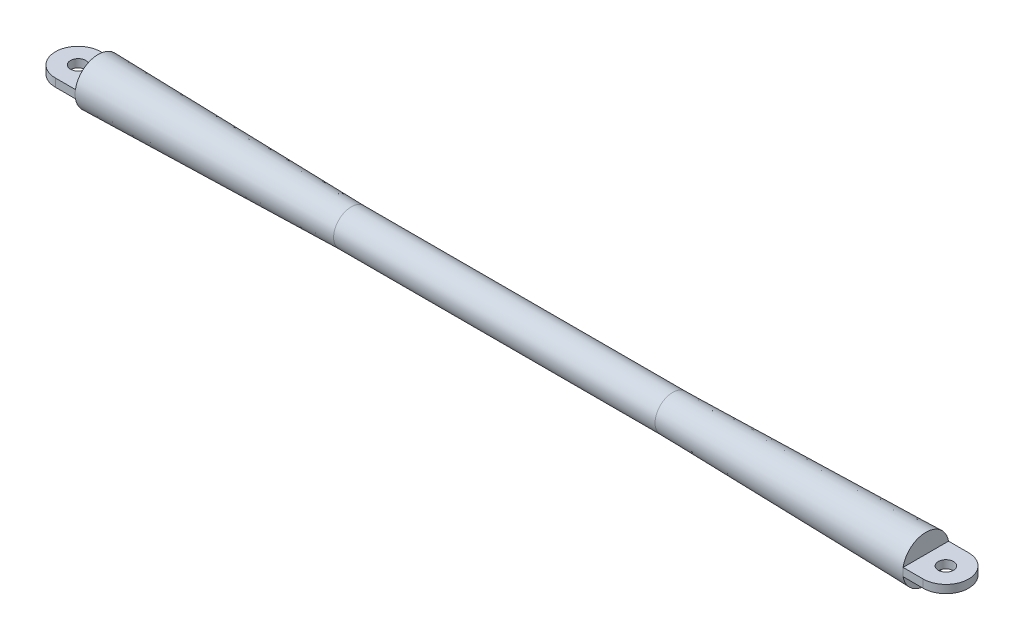
SolidWorks part; units mm, degrees
ref_plane "Front Plane" through (0, 0, 0) normal (0, 0, 1) x (1, 0, 0)
ref_plane "Top Plane" through (0, 0, 0) normal (0, 1, 0) x (1, 0, 0)
ref_plane "Right Plane" through (0, 0, 0) normal (1, 0, 0) x (0, 0, -1)
sketch "Sketch2" plane through (0, 0, 0) normal (0, 1, 0) x (1, 0, 0)
  line L0 (0, 0) -> (575, 0)
  line L1 (575, 0) -> (575, 30)
  line L2 (575, 30) -> (200, 22)
  line L3 (200, 22) -> (0, 22)
  line L4 (0, 22) -> (0, 0)
  point P3 (200.3181, 59.7349)
  dimension "D1" = 575
  dimension "D2" = 30
  dimension "D3" = 22
  dimension "D4" = 200
revolve "Revolve1" add sketch "Sketch2" angle 360 about L0
sketch "Sketch3" plane through (0, 0, 0) normal (0, 0, 1) x (1, 0, 0)
  line L0 (575, 0) -> (623.0835, 0) construction
  line L1 (515, 74.7561) -> (615.5423, 74.7561)
  line L2 (515, 74.7561) -> (515, 5)
  line L3 (515, 5) -> (615.5423, 5)
  line L4 (615.5423, 74.7561) -> (615.5423, 5)
  line L5 (575, -30) -> (575, 30) construction
  line L6 (515, -5) -> (615.5423, -5)
  line L7 (615.5423, -74.7561) -> (615.5423, -5)
  line L8 (515, -74.7561) -> (615.5423, -74.7561)
  line L9 (515, -74.7561) -> (515, -5)
  dimension "D1" = 10
  dimension "D2" = 60
extrude "Cut-Extrude1" cut sketch "Sketch3" against normal mid plane 100
sketch "Sketch4" plane through (0, 5, 0) normal (0, 1, 0) x (1, 0, 0)
  line L0 (515, 28.2814) -> (540, 28.2814)
  line L1 (515, -28.2814) -> (540, -28.2814)
  line L2 (515, 28.2814) -> (515, -28.2814) construction
  line L3 (515, 28.2814) -> (515, 50.0204)
  line L4 (515, 50.0204) -> (609.7801, 50.0204)
  line L5 (609.7801, 50.0204) -> (609.7801, -51.2095)
  line L6 (609.7801, -51.2095) -> (515, -51.2095)
  line L7 (515, -51.2095) -> (515, -28.2814)
  arc A0 (540, 28.2814) -> (540, -28.2814) centre (540, 0) cw
  dimension "D1" = 25
extrude "Cut-Extrude2" cut sketch "Sketch4" against normal mid plane 100
sketch "Sketch5" plane through (0, 5, 0) normal (0, 1, 0) x (1, 0, 0)
  circle A0 centre (540, 0) radius 9.5
  dimension "D1" = 19
extrude "Cut-Extrude3" cut sketch "Sketch5" against normal through all contours A0
mirror "Mirror1" about plane through (0, 0, -22) normal (1, 0, 0) of bodies 104
